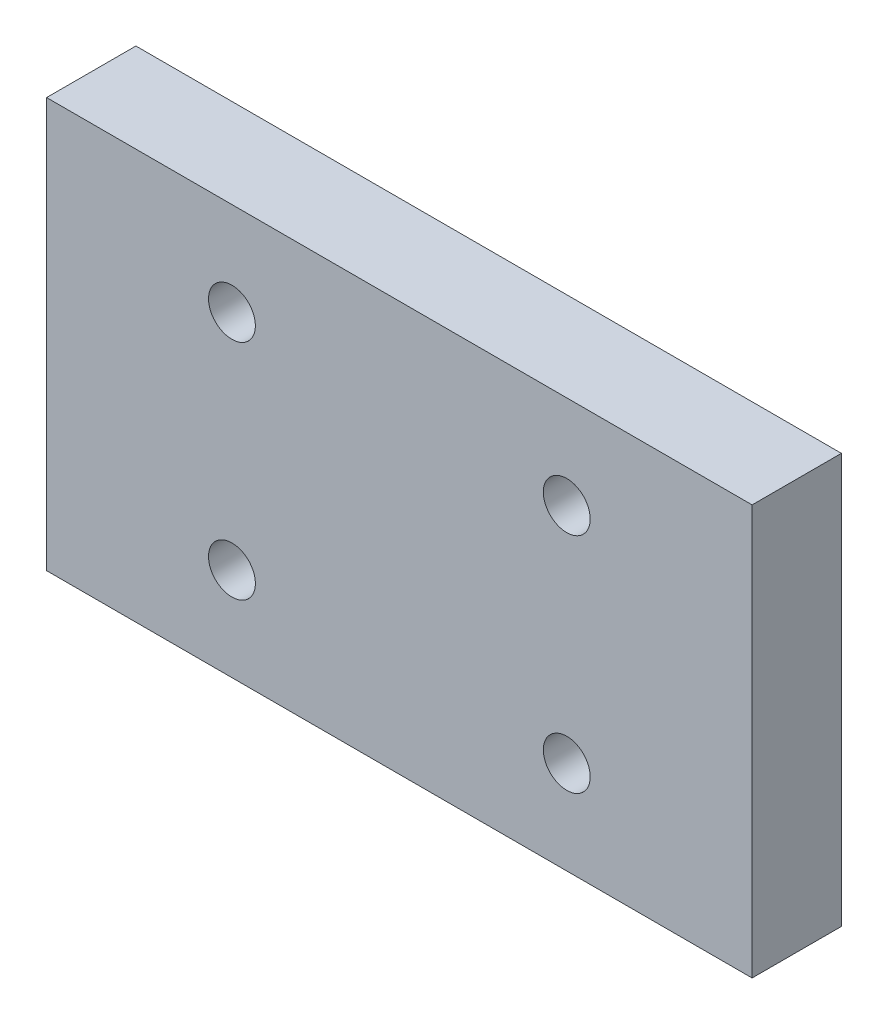
SolidWorks part; units mm, degrees
ref_plane "前视基准面" through (0, 0, 0) normal (0, 0, 1) x (1, 0, 0)
ref_plane "上视基准面" through (0, 0, 0) normal (0, 1, 0) x (1, 0, 0)
ref_plane "右视基准面" through (0, 0, 0) normal (1, 0, 0) x (0, 0, -1)
sketch "Sketch1" plane through (0, 0, 0) normal (0, 0, 1) x (1, 0, 0)
  line L0 (11.1455, -146) -> (41.1455, -166) construction
  line L1 (41.1455, -146) -> (11.1455, -146) construction
  line L2 (41.1455, -146) -> (41.1455, -166) construction
  line L3 (41.1455, -166) -> (11.1455, -166) construction
  line L4 (11.1455, -146) -> (11.1455, -166) construction
  line L6 (-5.4604, -137.6441) -> (57.7514, -137.6441)
  line L7 (-5.4604, -137.6441) -> (-5.4604, -174.3559)
  line L8 (-5.4604, -174.3559) -> (57.7514, -174.3559)
  line L9 (57.7514, -137.6441) -> (57.7514, -174.3559)
  line L10 (26.1455, -174.3559) -> (26.1455, -137.6441) construction
  line L11 (-5.4604, -156) -> (57.7514, -156) construction
  circle A4 centre (11.1455, -146) radius 2.1
  circle A5 centre (41.1455, -146) radius 2.1
  circle A6 centre (11.1455, -166) radius 2.1
  circle A7 centre (41.1455, -166) radius 2.1
  point P8 (26.1455, -156)
  dimension "D3" = 4.2
  dimension "D1" = 30
  dimension "D2" = 20
extrude "Boss-Extrude1" add sketch "Sketch1" along normal blind 8
